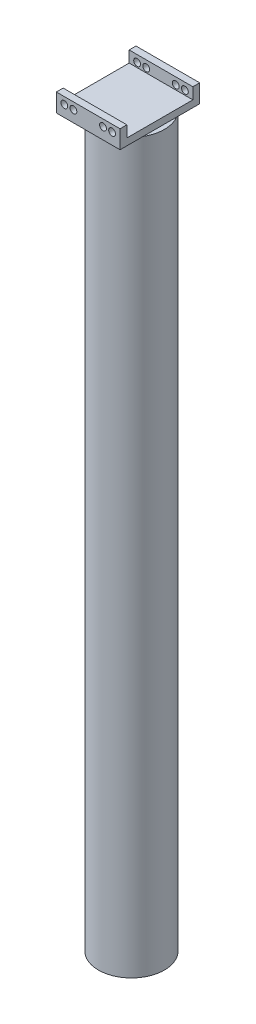
SolidWorks part; units mm, degrees
ref_plane "Front Plane" through (0, 0, 0) normal (0, 0, 1) x (1, 0, 0)
ref_plane "Top Plane" through (0, 0, 0) normal (0, 1, 0) x (1, 0, 0)
ref_plane "Right Plane" through (0, 0, 0) normal (1, 0, 0) x (0, 0, -1)
sketch "Sketch1" plane through (0, 0, 0) normal (0, 1, 0) x (1, 0, 0)
  circle A0 centre (0, 0) radius 14.5
  dimension "D1" = 29
extrude "Boss-Extrude1" add sketch "Sketch1" along normal blind 320
shell "Shell1" thickness 3
sketch "Sketch2" plane through (0, 0, 0) normal (0, 0, 1) x (1, 0, 0)
  line L1 (-15.5, 328) -> (12.5, 328)
  line L2 (-15.5, 328) -> (-15.5, 320)
  line L3 (-15.5, 320) -> (12.5, 320)
  line L4 (12.5, 328) -> (12.5, 320)
  line L7 (11.5, 320) -> (-11.5, 320) construction
  line L8 (14.5, 0) -> (14.5, 320) construction
  dimension "D1" = 28
  dimension "D2" = 8
  dimension "D3" = 0
  dimension "D4" = 2
extrude "Boss-Extrude2" add sketch "Sketch2" along normal mid plane 35
sketch "Sketch4" plane through (12.5, 0, 0) normal (1, 0, 0) x (0, 0, -1)
  line L0 (-17.5, 328) -> (17.5, 328) construction
  line L1 (-14.5, 328) -> (14.5, 328)
  line L2 (-14.5, 328) -> (-14.5, 323)
  line L3 (-14.5, 323) -> (14.5, 323)
  line L4 (14.5, 328) -> (14.5, 323)
  line L5 (-17.5, 320) -> (-17.5, 328) construction
  line L6 (7.3485, 320) -> (-7.3485, 320) construction
  line L7 (17.5, 320) -> (17.5, 328) construction
  dimension "D1" = 3
  dimension "D2" = 3
  dimension "D3" = 3
extrude "Cut-Extrude1" cut sketch "Sketch4" against normal up to surface (28 mm away) up to face at (-15.5, 324, 0)
sketch "Sketch5" plane through (0, 0, 17.5) normal (0, 0, 1) x (1, 0, 0)
  line L0 (12.5, 328) -> (-15.5, 328) construction
  circle A0 centre (-8, 325) radius 1.5
  circle A1 centre (5, 325) radius 1.5
  circle A2 centre (9, 325) radius 1.5
  circle A3 centre (-12, 325) radius 1.5
  point P10 (-1.5, 328)
  dimension "D1" = 13
  dimension "D2" = 21
  dimension "D3" = 3
  dimension "D4" = 3
  dimension "D5" = 3
  dimension "D6" = 3
  dimension "D8" = 10.5
  dimension "D9" = 3
  dimension "D7" = 4
extrude "Cut-Extrude2" cut sketch "Sketch5" against normal up to surface (35 mm away) up to face at (-1.5, 324, -17.5)
